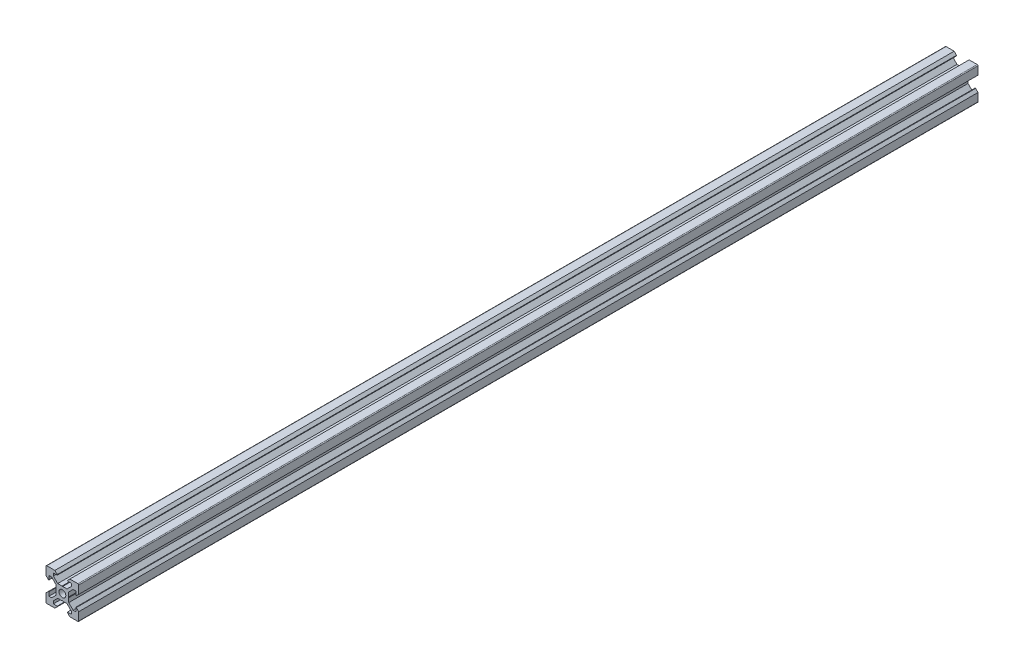
SolidWorks part; units mm, degrees
material "6061-T6 (SS)"
ref_plane "Front Plane" through (0, 0, 0) normal (0, 0, 1) x (1, 0, 0)
ref_plane "Top Plane" through (0, 0, 0) normal (0, 1, 0) x (1, 0, 0)
ref_plane "Right Plane" through (0, 0, 0) normal (1, 0, 0) x (0, 0, -1)
sketch "Sketch1" plane through (0, 0, 0) normal (0, 0, 1) x (1, 0, 0)
  line L1 (9.5, -10) -> (-9.5, -10)
  line L2 (10, -9.5) -> (10, 9.5)
  line L3 (9.5, 10) -> (-9.5, 10)
  line L4 (-10, -9.5) -> (-10, 9.5)
  line L5 (10, -10) -> (-10, 10) construction
  line L6 (10, 10) -> (-10, -10) construction
  circle A0 centre (0, 0) radius 2.1
  arc A1 (-9.5, 10) -> (-10, 9.5) centre (-9.5, 9.5) ccw
  arc A2 (10, 9.5) -> (9.5, 10) centre (9.5, 9.5) ccw
  arc A3 (9.5, -10) -> (10, -9.5) centre (9.5, -9.5) ccw
  arc A4 (-9.5, -10) -> (-10, -9.5) centre (-9.5, -9.5) cw
  point P0 (0, 0)
  line B0 (0, 0) -> (0, 10) construction
  line B1 (0, 3.69) -> (-0.21, 3.9)
  line B2 (-0.21, 3.9) -> (-2.8393, 3.9)
  line B3 (-2.8393, 3.9) -> (-5.5, 6.5607)
  line B4 (-5.5, 6.5607) -> (-5.5, 8.2)
  line B5 (-5.5, 8.2) -> (-3.125, 8.2)
  line B6 (-3.125, 8.2) -> (-3.125, 8.545)
  line B7 (-3.125, 8.545) -> (-4.58, 10)
  line B8 (-4.58, 10) -> (4.58, 10)
  line B9 (0, 0) -> (-5.9132, 5.9132) construction
  line B10 (3.125, 8.545) -> (4.58, 10)
  line B11 (3.125, 8.2) -> (3.125, 8.545)
  line B12 (5.5, 8.2) -> (3.125, 8.2)
  line B13 (5.5, 6.5607) -> (5.5, 8.2)
  line B14 (2.8393, 3.9) -> (5.5, 6.5607)
  line B15 (0.21, 3.9) -> (2.8393, 3.9)
  line B16 (0, 3.69) -> (0.21, 3.9)
  line B17 (0, 0) -> (-10, 0) construction
  line B18 (-3.69, 0) -> (-3.9, -0.21)
  line B19 (-3.9, -0.21) -> (-3.9, -2.8393)
  line B20 (-3.9, -2.8393) -> (-6.5607, -5.5)
  line B21 (-6.5607, -5.5) -> (-8.2, -5.5)
  line B22 (-8.2, -5.5) -> (-8.2, -3.125)
  line B23 (-8.2, -3.125) -> (-8.545, -3.125)
  line B24 (-8.545, -3.125) -> (-10, -4.58)
  line B25 (-10, -4.58) -> (-10, 4.58)
  line B26 (0, 0) -> (-5.9132, -5.9132) construction
  line B27 (-8.545, 3.125) -> (-10, 4.58)
  line B28 (-8.2, 3.125) -> (-8.545, 3.125)
  line B29 (-8.2, 5.5) -> (-8.2, 3.125)
  line B30 (-6.5607, 5.5) -> (-8.2, 5.5)
  line B31 (-3.9, 2.8393) -> (-6.5607, 5.5)
  line B32 (-3.9, 0.21) -> (-3.9, 2.8393)
  line B33 (-3.69, 0) -> (-3.9, 0.21)
  line B34 (0, 0) -> (0, -10) construction
  line B35 (0, -3.69) -> (0.21, -3.9)
  line B36 (0.21, -3.9) -> (2.8393, -3.9)
  line B37 (2.8393, -3.9) -> (5.5, -6.5607)
  line B38 (5.5, -6.5607) -> (5.5, -8.2)
  line B39 (5.5, -8.2) -> (3.125, -8.2)
  line B40 (3.125, -8.2) -> (3.125, -8.545)
  line B41 (3.125, -8.545) -> (4.58, -10)
  line B42 (4.58, -10) -> (-4.58, -10)
  line B43 (0, 0) -> (5.9132, -5.9132) construction
  line B44 (-3.125, -8.545) -> (-4.58, -10)
  line B45 (-3.125, -8.2) -> (-3.125, -8.545)
  line B46 (-5.5, -8.2) -> (-3.125, -8.2)
  line B47 (-5.5, -6.5607) -> (-5.5, -8.2)
  line B48 (-2.8393, -3.9) -> (-5.5, -6.5607)
  line B49 (-0.21, -3.9) -> (-2.8393, -3.9)
  line B50 (0, -3.69) -> (-0.21, -3.9)
  line B51 (0, 0) -> (10, 0) construction
  line B52 (3.69, 0) -> (3.9, 0.21)
  line B53 (3.9, 0.21) -> (3.9, 2.8393)
  line B54 (3.9, 2.8393) -> (6.5607, 5.5)
  line B55 (6.5607, 5.5) -> (8.2, 5.5)
  line B56 (8.2, 5.5) -> (8.2, 3.125)
  line B57 (8.2, 3.125) -> (8.545, 3.125)
  line B58 (8.545, 3.125) -> (10, 4.58)
  line B59 (10, 4.58) -> (10, -4.58)
  line B60 (0, 0) -> (5.9132, 5.9132) construction
  line B61 (8.545, -3.125) -> (10, -4.58)
  line B62 (8.2, -3.125) -> (8.545, -3.125)
  line B63 (8.2, -5.5) -> (8.2, -3.125)
  line B64 (6.5607, -5.5) -> (8.2, -5.5)
  line B65 (3.9, -2.8393) -> (6.5607, -5.5)
  line B66 (3.9, -0.21) -> (3.9, -2.8393)
  line B67 (3.69, 0) -> (3.9, -0.21)
  dimension "D1" = 4.2
  dimension "D3" = 0.5
  dimension "D2" = 20
sketch_block_instance "V Slot 1-4"
sketch_block "V Slot 1" parameters "D1"=10, "D2"=11, "D3"=4.3, "D4"=1.8, "D5"=0.21, "D6"=45, "D7"=9.16, "D8"=1.5, "D9"=6.25
sketch_block_instance "V Slot 1-5"
sketch_block_instance "V Slot 1-6"
sketch_block_instance "V Slot 1-7"
extrude "Boss-Extrude1" add sketch "Sketch1" along normal blind 550 contours B67 B52 B53 B54 B55 B56 B57 B58 L2 A2 L3 B10 B11 B12 B13 B14 B15 B16 B1 B2 B3 B4 B5 B6 B7 A1 L4 B27 B28 B29 B30 B31 B32 B33 B18 B19 B20 B21 B22 B23 B24 A4 L1 B44 B45 B46 B47 B48 B49
